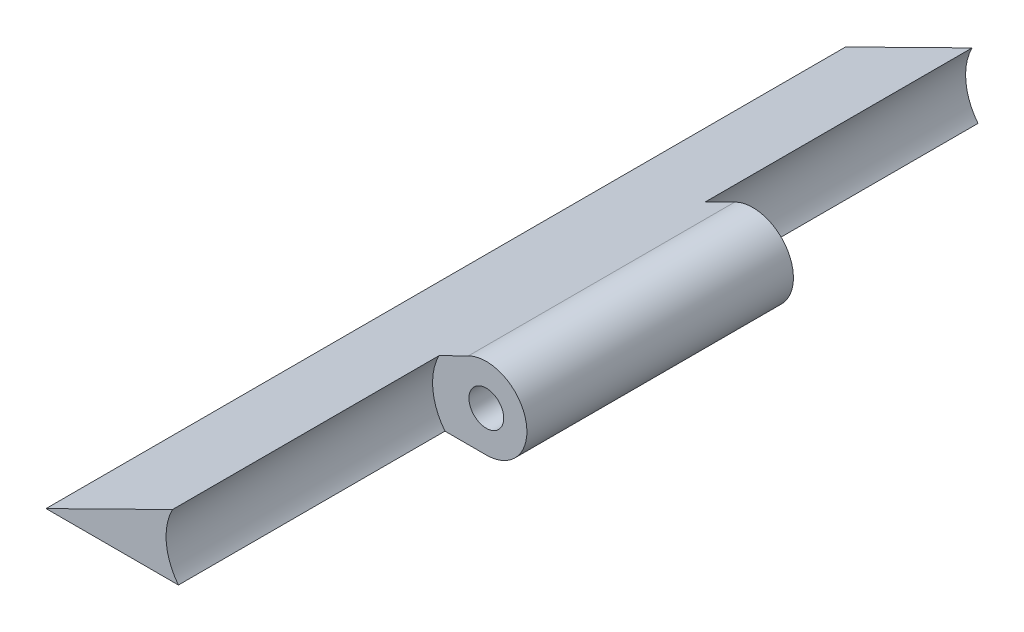
SolidWorks part; units mm, degrees
ref_plane "Front Plane" through (0, 0, 0) normal (0, 0, 1) x (1, 0, 0)
ref_plane "Top Plane" through (0, 0, 0) normal (0, 1, 0) x (1, 0, 0)
ref_plane "Right Plane" through (0, 0, 0) normal (1, 0, 0) x (0, 0, -1)
sketch "Sketch1" plane through (0, 0, 0) normal (0, 0, 1) x (1, 0, 0)
  circle A0 centre (0, 0) radius 3.5
  circle A1 centre (0, 0) radius 1.5
  dimension "D1" = 7
  dimension "D2" = 2
extrude "Boss-Extrude1" add sketch "Sketch1" along normal mid plane 23
sketch "Sketch2" plane through (0, 0, 0) normal (0, 0, 1) x (1, 0, 0)
  line L0 (0, -3.5) -> (-15, -3.5)
  line L1 (-15, -3.5) -> (-1.549, 3.1386)
  line L2 (0, 0) -> (0, -3.5) construction
  circle A0 centre (0, 0) radius 3.5 construction
  arc A1 (-1.549, 3.1386) -> (0, -3.5) centre (0, 0) ccw
  dimension "D1" = 15
extrude "Boss-Extrude2" add sketch "Sketch2" along normal mid plane 23
sketch "Sketch3" plane through (0, 0, 0) normal (0, 0, -1) x (-1, 0, 0)
  line L0 (3.5707, -3.5) -> (15, -3.5)
  line L1 (15, -3.5) -> (0, -3.5) construction
  line L2 (15, -3.5) -> (4.0814, 1.8887)
  line L3 (1.549, 3.1386) -> (15, -3.5) construction
  circle A0 centre (0, 0) radius 3.5 construction
  arc A1 (1.549, 3.1386) -> (0, -3.5) centre (0, 0) ccw construction
  arc A2 (4.0814, 1.8887) -> (3.5707, -3.5) centre (-0.3594, -0.409) cw
  point P15 (0, 0)
  point P16 (4.0814, 1.8887)
  dimension "D1" = 5
extrude "Boss-Extrude3" add sketch "Sketch3" along normal mid plane 69
